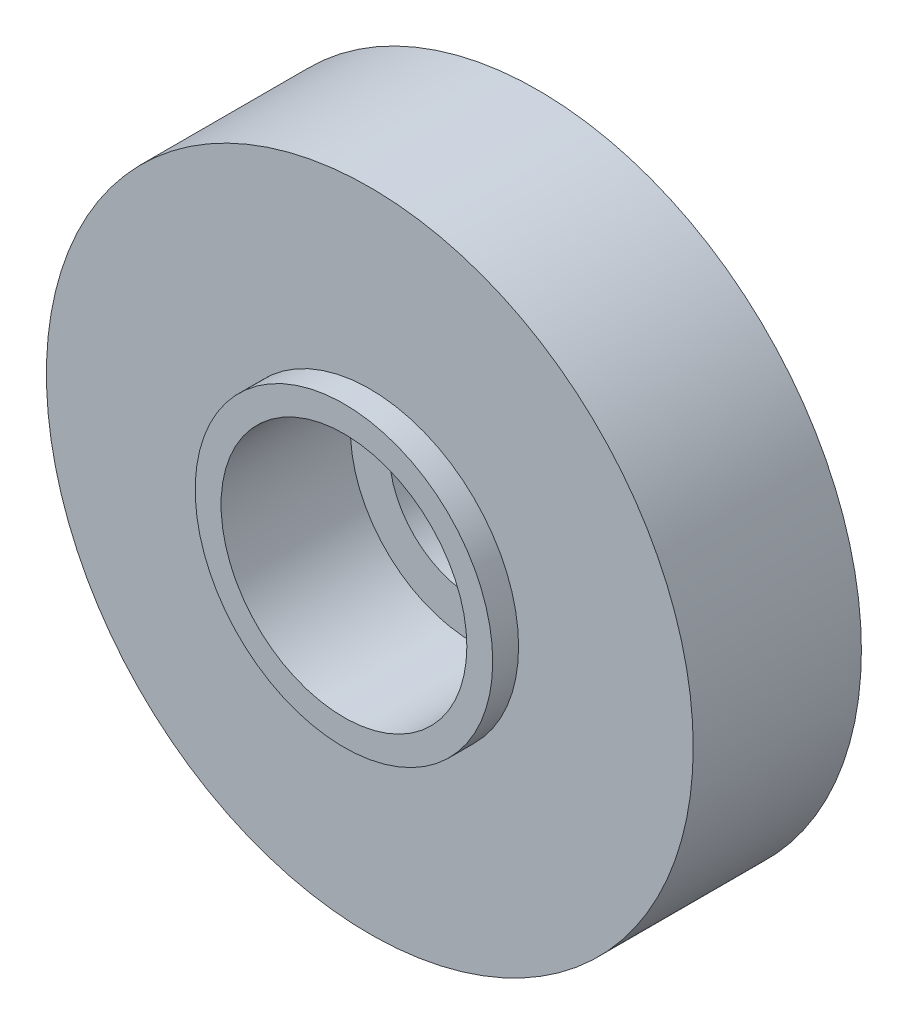
SolidWorks part; units mm, degrees
ref_plane "Alzado" through (0, 0, 0) normal (0, 0, 1) x (1, 0, 0)
ref_plane "Planta" through (0, 0, 0) normal (0, 1, 0) x (1, 0, 0)
ref_plane "Vista lateral" through (0, 0, 0) normal (1, 0, 0) x (0, 0, -1)
sketch "Croquis1" plane through (0, 0, 0) normal (0, 0, 1) x (1, 0, 0)
  circle A0 centre (0, 0) radius 25
  dimension "D1" = 50
extrude "Saliente-Extruir1" add sketch "Croquis1" against normal blind 13
sketch "Croquis2" plane through (0, 0, 0) normal (0, 0, 1) x (1, 0, 0)
  circle A0 centre (0, 0) radius 11.5
  dimension "D1" = 23
extrude "Saliente-Extruir2" add sketch "Croquis2" along normal blind 2 contours A0
sketch "Croquis3" plane through (0, 0, 2) normal (0, 0, 1) x (1, 0, 0)
  circle A0 centre (0, 0) radius 9.5
  dimension "D1" = 19
extrude "Cortar-Extruir1" cut sketch "Croquis3" against normal blind 10
sketch "Croquis4" plane through (0, 0, -8) normal (0, 0, 1) x (1, 0, 0)
  circle A0 centre (0, 0) radius 6.5
  dimension "D1" = 13
extrude "Cortar-Extruir2" cut sketch "Croquis4" against normal through all
